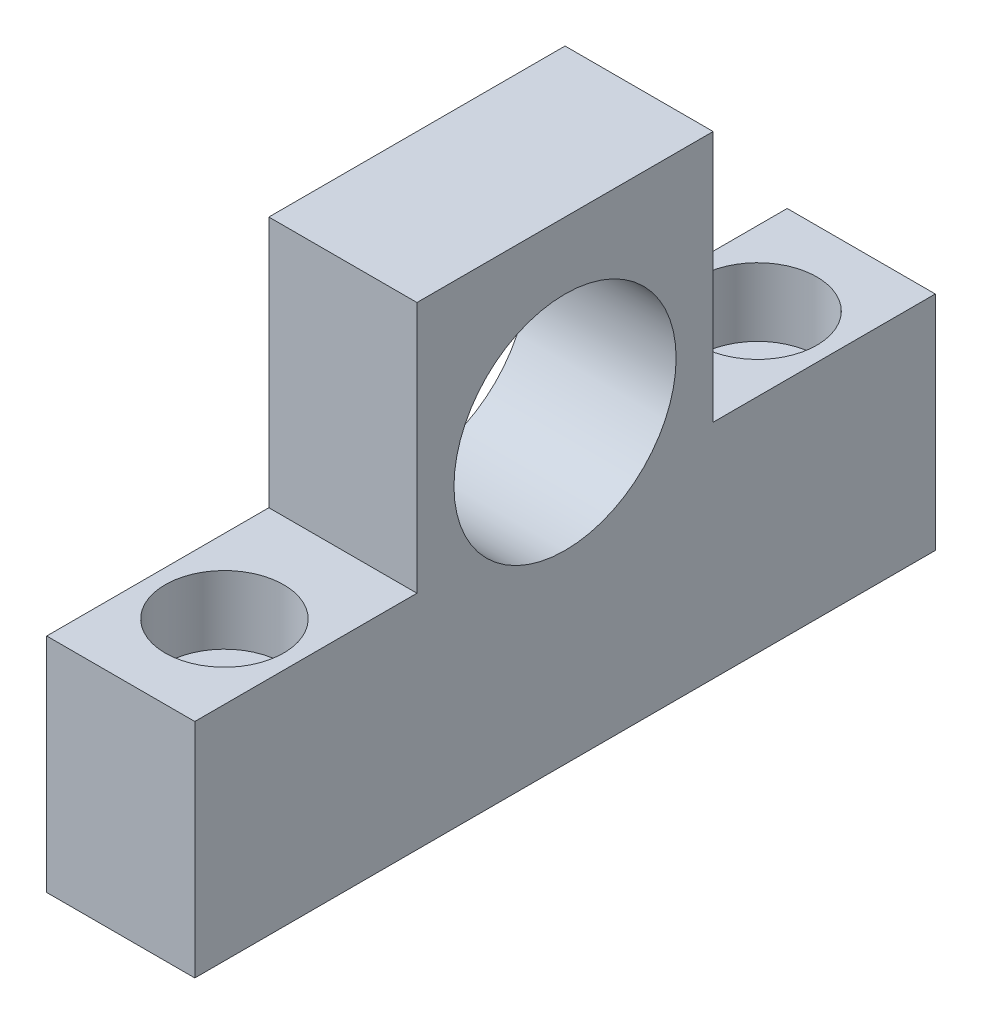
SolidWorks part; units mm, degrees
ref_plane "前视基准面" through (0, 0, 0) normal (0, 0, 1) x (1, 0, 0)
ref_plane "上视基准面" through (0, 0, 0) normal (0, 1, 0) x (1, 0, 0)
ref_plane "右视基准面" through (0, 0, 0) normal (1, 0, 0) x (0, 0, -1)
other "Configuration Table"
sketch "草图1" plane through (0, 0, 0) normal (1, 0, 0) x (0, 0, -1)
  line L0 (0, 0) -> (50, 0)
  line L1 (50, 0) -> (50, 15)
  line L2 (50, 15) -> (35, 15)
  line L3 (35, 15) -> (35, 32)
  line L4 (35, 32) -> (15, 32)
  line L5 (15, 32) -> (15, 15)
  line L6 (15, 15) -> (0, 15)
  line L7 (0, 15) -> (0, 0)
  line L8 (25, 0) -> (25, 35.752) construction
  circle A0 centre (25, 20) radius 7.5
  dimension "D4" = 15
  dimension "D1" = 50
  dimension "D2" = 15
  dimension "D3" = 15
  dimension "D5" = 20
  dimension "D6" = 32
  dimension "D7" = 20
extrude "凸台-拉伸1" add sketch "草图1" along normal blind 10
sketch "草图2" plane through (0, 15, 0) normal (0, 1, 0) x (1, 0, 0)
  line L0 (10, 50) -> (0, 50) construction
  line L2 (0, 50) -> (0, 35) construction
  line L4 (0, 25) -> (16.7504, 25) construction
  line L5 (0, 35) -> (0, 15) construction
  circle A0 centre (5, 43) radius 2
  circle A1 centre (5, 7) radius 2
  dimension "D1" = 4
  dimension "D2" = 7
  dimension "D3" = 5
hole_wizard "M4 六角圆柱头螺钉的柱形沉头孔1" positions "3D草图1" profile "草图3" counterbore size "M4" standard "GB" end condition through all
sketch3d "3D草图1"
  point P0 (5, 15, -43)
  point P3 (5, 15, -7)
sketch "草图3" plane through (5, 15, -43) normal (1, 0, 0) x (0, 0, 1)
  line L0 (0, 0) -> (0, 15)
  line L1 (0, 15) -> (2.25, 15)
  line L3 (2.25, 15) -> (2.25, 4.6)
  line L4 (2.25, 4.6) -> (4, 4.6)
  line L5 (4, 4.6) -> (4, 0)
  line L7 (4, 0) -> (0, 0)
  line L11 (0, -6.35) -> (0, 107.95) construction
  dimension "通孔孔直径" = 4.5
  dimension "通孔孔深度" = 15
  dimension "柱形沉头孔直径" = 8
  dimension "柱形沉头孔深度" = 4.6
